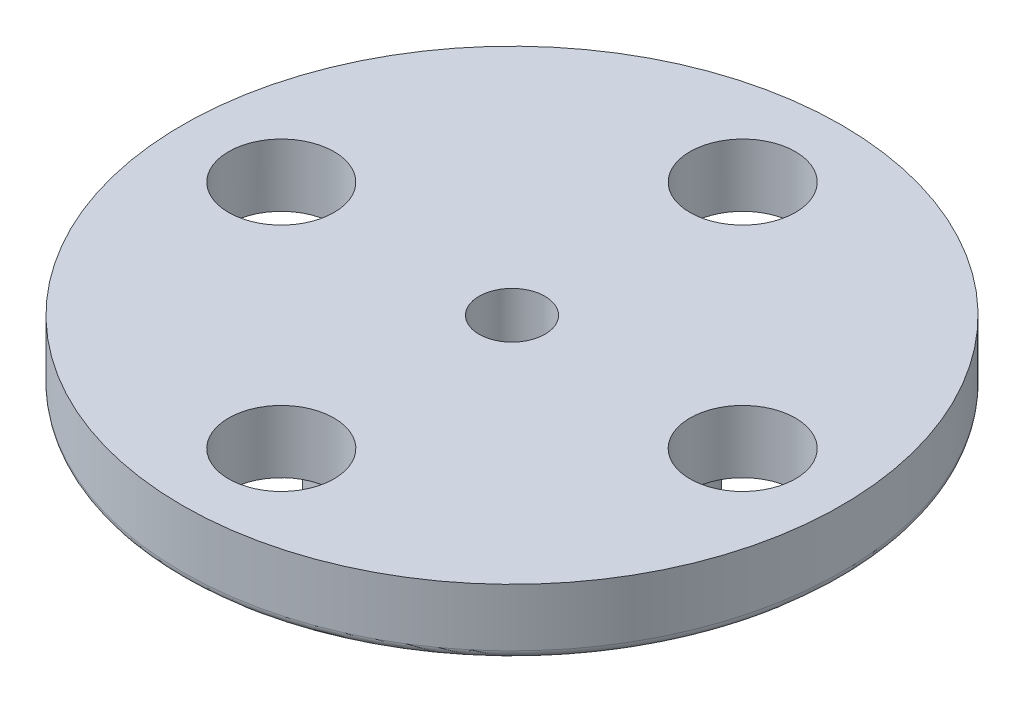
SolidWorks part; units mm, degrees
material "ABS"
ref_plane "Front Plane" through (0, 0, 0) normal (0, 0, 1) x (1, 0, 0)
ref_plane "Top Plane" through (0, 0, 0) normal (0, 1, 0) x (1, 0, 0)
ref_plane "Right Plane" through (0, 0, 0) normal (1, 0, 0) x (0, 0, -1)
sketch "Sketch1" plane through (0, 0, 0) normal (0, 1, 0) x (1, 0, 0)
  circle A0 centre (0, 0) radius 10
  dimension "D1" = 20
extrude "Boss-Extrude1" add sketch "Sketch1" along normal blind 2
sketch "Sketch2" plane through (0, 0, 0) normal (0, 1, 0) x (1, 0, 0)
  circle A0 centre (0, 0) radius 4.5
  dimension "D1" = 9
extrude "Boss-Extrude2" add sketch "Sketch2" against normal blind 2.5
sketch "Sketch3" plane through (0, 0, 0) normal (0, 1, 0) x (1, 0, 0)
  line L0 (0, 16.6668) -> (0, -17.2828) construction
  line L1 (-21.9372, 0) -> (30.2192, 0) construction
  line L2 (-7, 16.6668) -> (-7, -16.6668) construction
  line L3 (-15.9139, 7) -> (17.4197, 7) construction
  circle A0 centre (0, 7) radius 1.6
  circle A1 centre (-7, 0) radius 1.6
  circle A2 centre (0, -7) radius 1.6
  circle A3 centre (7, 0) radius 1.6
  dimension "D3" = 3.2
  dimension "D4" = 3.2
  dimension "D1" = 7
  dimension "D2" = 7
fillet "Fillet1" radius 0.25 1 edges at (0, 0, 10)
sketch "Sketch6" plane through (0, 2, 0) normal (0, 1, 0) x (1, 0, 0)
  circle A0 centre (0, 0) radius 1
  dimension "D1" = 2
extrude "Cut-Extrude2" cut sketch "Sketch6" against normal through all
sketch "Sketch7" plane through (0, -2.5, 0) normal (0, -1, 0) x (1, 0, 0)
  circle A0 centre (0, 0) radius 2.9
  dimension "D1" = 5.8
extrude "Cut-Extrude3" cut sketch "Sketch7" against normal blind 2.5
sketch3d "3DSketch1"
  line L0 (0, 0, 0) -> (0, -47.4119, 0) construction
sketch "Sketch8" plane through (0, -2.5, 0) normal (0, -1, 0) x (1, 0, 0)
  line L1 (-2.3524, -1.0465) -> (-2.7456, -0.9337)
  line L2 (-2.3524, -1.0465) -> (-2.5319, -1.4141)
  arc A1 (-2.7456, -0.9337) -> (-2.5319, -1.4141) centre (0, 0) ccw
  circle A4 centre (0, 0) radius 2.9 construction
  dimension "D4" = 0.409
  dimension "D3" = 5.8
  dimension "D1" = 80
  dimension "D2" = 0.5258
extrude "Boss-Extrude4" add sketch "Sketch8" against normal blind 2.5
pattern_circular "CirPattern1" count 26 over 360 about axis through (0, 0, 0) along (0, 1, 0) of "Boss-Extrude4"
extrude "Cut-Extrude4" cut sketch "Sketch3" along normal through all
sketch "Sketch9" plane through (0, -2.5, 0) normal (0, -1, 0) x (1, 0, 0)
  circle A0 centre (7, 0) radius 3.25
  circle A1 centre (0, -7) radius 3.25
  circle A2 centre (-7, 0) radius 3.25
  circle A3 centre (0, 7) radius 3.25
  point P12 (0, 0)
  dimension "D1" = 6.5
  dimension "D2" = 4
extrude "Cut-Extrude5" cut sketch "Sketch9" against normal blind 2.6
